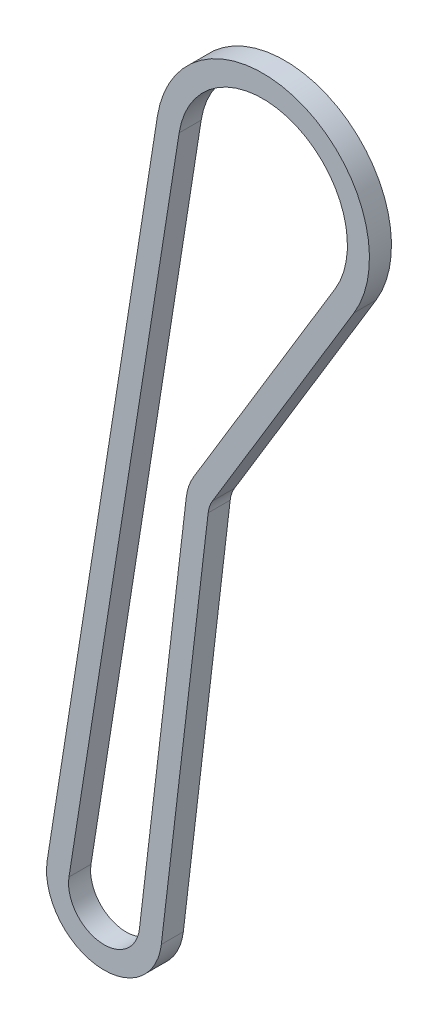
SolidWorks part; units mm, degrees
material "NEOPRENE"
ref_plane "Front Plane" through (0, 0, 0) normal (0, 0, 1) x (1, 0, 0)
ref_plane "Top Plane" through (0, 0, 0) normal (0, 1, 0) x (1, 0, 0)
ref_plane "Right Plane" through (0, 0, 0) normal (1, 0, 0) x (0, 0, -1)
sketch "Sketch2" plane through (0, 0, 0) normal (0, 0, 1) x (1, 0, 0)
  line L0 (0, 0) -> (1, 0) construction
  line L1 (0, 0) -> (0, 1) construction
  line L2 (-21.6346, -3.9354) -> (3.361, 154.7975)
  line L4 (47.9836, 138.4883) -> (15.8517, 85.4429)
  line L5 (14.8871, 82.6361) -> (4.2564, -7.4993)
  arc A0 (4.2564, -7.4993) -> (-21.6346, -3.9354) centre (-8.7237, -5.9684) cw
  arc A1 (3.361, 154.7975) -> (47.9836, 138.4883) centre (27.2763, 151.0316) cw
  arc A2 (15.8517, 85.4429) -> (14.8871, 82.6361) centre (21.8389, 81.8162) ccw
extrude "Extrude-Thin1" add sketch "Sketch2" against normal blind 5 thin
